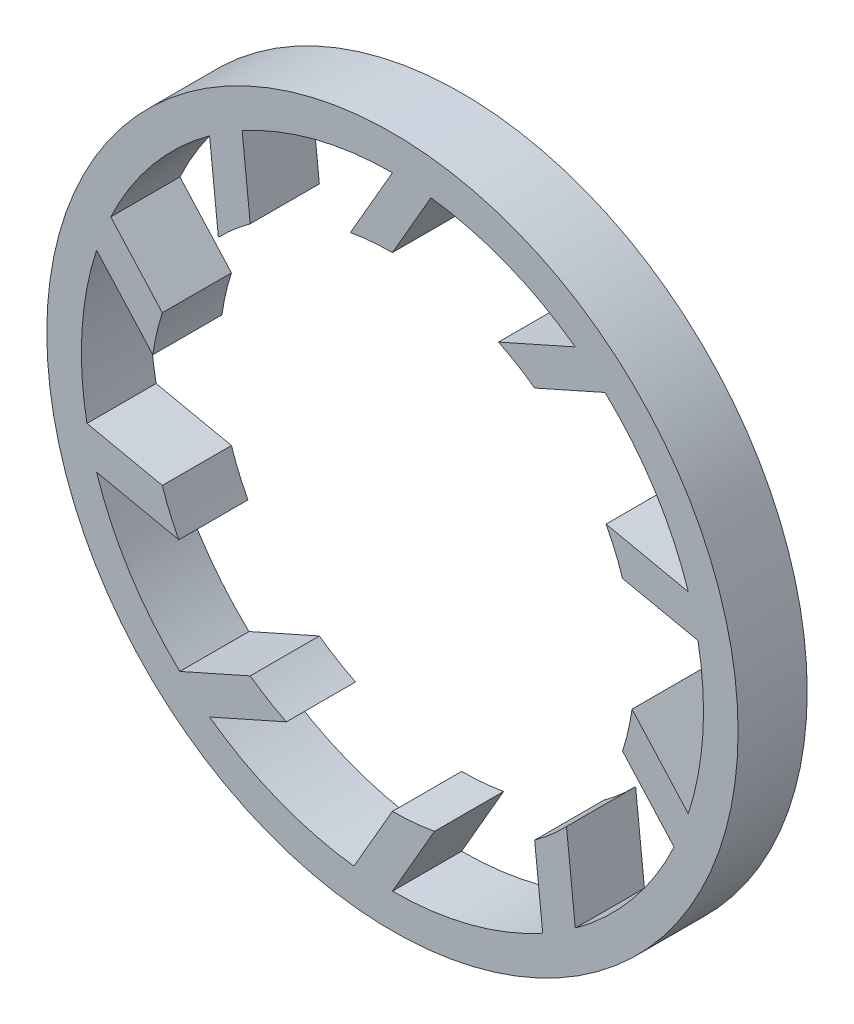
SolidWorks part; units mm, degrees
ref_plane "Front Plane" through (0, 0, 0) normal (0, 0, 1) x (1, 0, 0)
ref_plane "Top Plane" through (0, 0, 0) normal (0, 1, 0) x (1, 0, 0)
ref_plane "Right Plane" through (0, 0, 0) normal (1, 0, 0) x (0, 0, -1)
sketch "Sketch1" plane through (0, 0, 0) normal (0, 0, 1) x (1, 0, 0)
  line L0 (-1000, 0) -> (49000, 0) construction
  line L1 (0, -1000) -> (0, 49000) construction
  line L2 (0, 22.5) -> (-3.0404, 17.2339)
  line L3 (0, 17.5) -> (2.7867, 22.3268)
  line L4 (13.2252, 18.2029) -> (7.6701, 15.7296)
  line L5 (10.2862, 14.1578) -> (15.3779, 16.4247)
  line L6 (21.3988, 6.9529) -> (15.4508, 8.2172)
  line L7 (16.6435, 5.4078) -> (22.0952, 4.249)
  line L8 (21.3988, -6.9529) -> (17.3299, -2.434)
  line L9 (16.6435, -5.4078) -> (20.3729, -9.5497)
  line L10 (13.2252, -18.2029) -> (12.5895, -12.1554)
  line L11 (10.2862, -14.1578) -> (10.8688, -19.7007)
  line L12 (0, -22.5) -> (3.0404, -17.2339)
  line L13 (0, -17.5) -> (-2.7867, -22.3268)
  line L14 (-13.2252, -18.2029) -> (-7.6701, -15.7296)
  line L15 (-10.2862, -14.1578) -> (-15.3779, -16.4247)
  line L16 (-21.3988, -6.9529) -> (-15.4508, -8.2172)
  line L17 (-16.6435, -5.4078) -> (-22.0952, -4.249)
  line L18 (-21.3988, 6.9529) -> (-17.3299, 2.434)
  line L19 (-16.6435, 5.4078) -> (-20.3729, 9.5497)
  line L20 (-13.2252, 18.2029) -> (-12.5895, 12.1554)
  line L21 (-10.2862, 14.1578) -> (-10.8688, 19.7007)
  circle A0 centre (0, 0) radius 25
  arc A1 (21.3988, -6.9529) -> (22.0952, 4.249) centre (0, 0) ccw
  arc A2 (-10.2862, 14.1578) -> (-12.5895, 12.1554) centre (0, 0) ccw
  arc A3 (0, 17.5) -> (-3.0404, 17.2339) centre (0, 0) ccw
  arc A4 (10.2862, 14.1578) -> (7.6701, 15.7296) centre (0, 0) ccw
  arc A5 (16.6435, 5.4078) -> (15.4508, 8.2172) centre (0, 0) ccw
  arc A6 (-16.6435, 5.4078) -> (-17.3299, 2.434) centre (0, 0) ccw
  arc A7 (-16.6435, -5.4078) -> (-15.4508, -8.2172) centre (0, 0) ccw
  arc A8 (-10.2862, -14.1578) -> (-7.6701, -15.7296) centre (0, 0) ccw
  arc A9 (0, -17.5) -> (3.0404, -17.2339) centre (0, 0) ccw
  arc A10 (10.2862, -14.1578) -> (12.5895, -12.1554) centre (0, 0) ccw
  arc A11 (16.6435, -5.4078) -> (17.3299, -2.434) centre (0, 0) ccw
  arc A12 (21.3988, 6.9529) -> (15.3779, 16.4247) centre (0, 0) ccw
  arc A13 (13.2252, 18.2029) -> (2.7867, 22.3268) centre (0, 0) ccw
  arc A14 (0, 22.5) -> (-10.8688, 19.7007) centre (0, 0) ccw
  arc A15 (-13.2252, 18.2029) -> (-20.3729, 9.5497) centre (0, 0) ccw
  arc A16 (-21.3988, 6.9529) -> (-22.0952, -4.249) centre (0, 0) ccw
  arc A17 (-21.3988, -6.9529) -> (-15.3779, -16.4247) centre (0, 0) ccw
  arc A18 (-13.2252, -18.2029) -> (-2.7867, -22.3268) centre (0, 0) ccw
  arc A19 (0, -22.5) -> (10.8688, -19.7007) centre (0, 0) ccw
  arc A20 (13.2252, -18.2029) -> (20.3729, -9.5497) centre (0, 0) ccw
  point P53 (0, 0)
  dimension "D1" = 50
  dimension "D2" = 45
  dimension "D3" = 35
  dimension "D4" = 30
  dimension "D5" = 10
extrude "Boss-Extrude2" add sketch "Sketch1" along normal mid plane 5
scale "Scale1" scale about centroid uniform scaling yes scale factor 1.5
